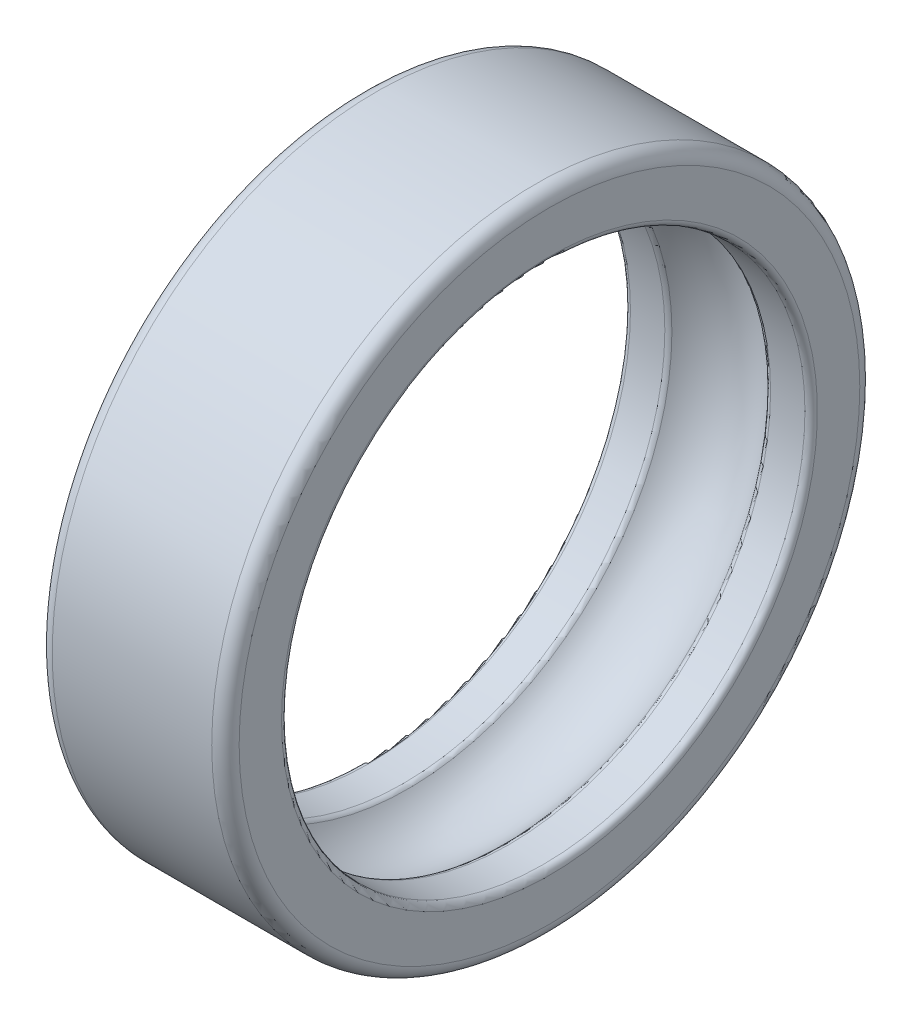
SolidWorks part; units mm, degrees
ref_plane "Front Plane" through (0, 0, 0) normal (1, 0, 0) x (0, 1, 0)
ref_plane "Top Plane" through (0, 0, 0) normal (0, 0, 1) x (0, 1, 0)
ref_plane "Right Plane" through (0, 0, 0) normal (0, 1, 0) x (-1, 0, 0)
sketch "Sketch1" plane through (0, 0, 0) normal (0, 1, 0) x (-1, 0, 0)
  line L0 (-12.9439, 0) -> (12.9439, 0) construction
  line L1 (-7.5, 21) -> (-7.5, 26)
  line L2 (-7.5, 26) -> (7.5, 26)
  line L3 (7.5, 26) -> (7.5, 21)
  line L4 (7.5, 21) -> (4, 21)
  line L5 (-4, 21) -> (-7.5, 21)
  arc A0 (4, 21) -> (-4, 21) centre (0, 18) ccw
  point P2 (0, 0)
  point P10 (0, 26)
  dimension "D2" = 3
  dimension "D3" = 10
  dimension "D1" = 5
  dimension "D4" = 15
  dimension "D5" = 26
revolve "Revolve1" add sketch "Sketch1" angle 360 about L0
fillet "Fillet1" radius 1.1 2 edges at (-7.5, 0, -26) (7.5, 0, -26)
fillet "Fillet2" radius 0.5 4 edges at (-7.5, 0, -21) (-4, 0, -21) (4, 0, -21) (7.5, 0, -21)
